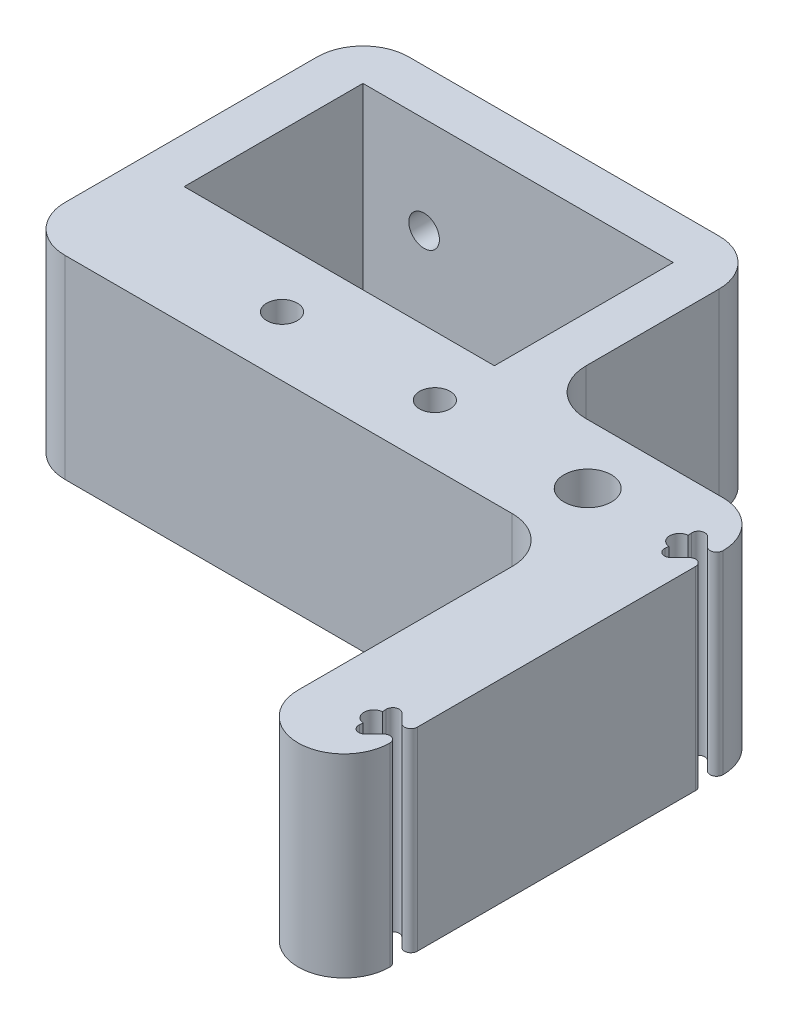
SolidWorks part; units mm, degrees
material "6061 Alloy"
ref_plane "Front Plane" through (0, 0, 0) normal (0, 0, 1) x (1, 0, 0)
ref_plane "Top Plane" through (0, 0, 0) normal (0, 1, 0) x (1, 0, 0)
ref_plane "Right Plane" through (0, 0, 0) normal (1, 0, 0) x (0, 0, -1)
sketch "Sketch1" plane through (0, 0, 0) normal (0, 1, 0) x (1, 0, 0)
  line L0 (0, 0) -> (-4, 0) construction
  line L1 (-4, 0) -> (-4.0553, 0.6326) construction
  line L2 (-4.0553, 0.6326) -> (-4.0758, 0.8669)
  line L3 (-3.3615, 1.2) -> (-2.7615, 0.6)
  line L4 (-4, 0) -> (-3.0808, 0.9192) construction
  line L5 (-6.465, 0.8965) -> (-2.465, 0.8965) construction
  line L6 (-4.0553, -0.6326) -> (-4.0758, -0.8669)
  line L7 (-3.3615, -1.2) -> (-2.7615, -0.6)
  line L47 (-4.0553, 20.6326) -> (-4.0758, 20.8669)
  line L48 (-3.3615, 21.2) -> (-2.7615, 20.6)
  line L49 (-4.0553, 19.3674) -> (-4.0758, 19.1331)
  line L50 (-3.3615, 18.8) -> (-2.7615, 19.4)
  line L53 (-4, 20) -> (-4.0553, 20.6326) construction
  line L54 (-4, 20) -> (-3.0808, 20.9192) construction
  line L55 (-4.0553, 0.6326) -> (-4.0553, 20.6326) construction
  line L67 (-7.2335, 20) -> (-10.075, 20) construction
  line L72 (-2.0456, 0.8965) -> (-2.0456, 19.1035)
  line L73 (-20, 35.5965) -> (-20, 23.8965)
  line L74 (-5.0456, 23.8965) -> (-14, 23.8965)
  line L75 (-2.465, -0.8965) -> (-5.0456, -0.8965) construction
  line L76 (-5.0456, 20.8965) -> (-2.465, 20.8965) construction
  line L78 (-8.0456, -0.8965) -> (-8.0456, 13.1035)
  line L79 (-11.0456, 16.1035) -> (-40.3, 16.1035)
  line L81 (-17, 26.8965) -> (-17, 35.5965)
  line L82 (-20, 38.5965) -> (-40.3, 38.5965)
  line L83 (-20, 23.8965) -> (-40.3, 23.8965)
  line L84 (-20, 35.5965) -> (-40.3, 35.5965)
  line L87 (-40.3, 35.5965) -> (-40.3, 23.8965)
  line L88 (-43.3, 19.1035) -> (-43.3, 35.5965)
  line L89 (-10, 20) -> (-10, 23.8965) construction
  line L90 (-10, 20) -> (-10, 16.1035) construction
  circle A0 centre (-4, 0) radius 0.635 construction
  arc A1 (-4.0758, 0.8669) -> (-3.3615, 1.2) centre (-3.6581, 0.9035) cw
  arc A2 (-2.7615, 0.6) -> (-2.0456, 0.8965) centre (-2.465, 0.8965) ccw
  arc A4 (-4.0553, 0.6326) -> (-4.0553, -0.6326) centre (-4, 0) ccw
  arc A5 (-4.0758, -0.8669) -> (-3.3615, -1.2) centre (-3.6581, -0.9035) ccw
  arc A6 (-2.7615, -0.6) -> (-2.0456, -0.8965) centre (-2.465, -0.8965) cw
  arc A87 (-4.0758, 20.8669) -> (-3.3615, 21.2) centre (-3.6581, 20.9035) cw
  arc A88 (-2.7615, 20.6) -> (-2.0456, 20.8965) centre (-2.465, 20.8965) ccw
  arc A89 (-4.0553, 20.6326) -> (-4.0553, 19.3674) centre (-4, 20) ccw
  arc A90 (-4.0758, 19.1331) -> (-3.3615, 18.8) centre (-3.6581, 19.0965) ccw
  arc A91 (-2.7615, 19.4) -> (-2.0456, 19.1035) centre (-2.465, 19.1035) cw
  circle A92 centre (-4, 20) radius 0.635 construction
  arc A93 (-2.0456, -0.8965) -> (-8.0456, -0.8965) centre (-5.0456, -0.8965) cw
  arc A105 (-8.0456, 13.1035) -> (-11.0456, 16.1035) centre (-11.0456, 13.1035) ccw
  arc A110 (-2.0456, 20.8965) -> (-5.0456, 23.8965) centre (-5.0456, 20.8965) ccw
  circle A111 centre (-20, 20) radius 1
  circle A114 centre (-10, 20) radius 1.55
  arc A115 (-14, 23.8965) -> (-17, 26.8965) centre (-14, 26.8965) cw
  arc A116 (-17, 35.5965) -> (-20, 38.5965) centre (-20, 35.5965) ccw
  circle A118 centre (-30, 20) radius 1
  arc A119 (-40.3, 16.1035) -> (-43.3, 19.1035) centre (-40.3, 19.1035) cw
  arc A120 (-40.3, 38.5965) -> (-43.3, 35.5965) centre (-40.3, 35.5965) ccw
  point P0 (0, 0)
  dimension "D1" = 1.27
  dimension "D16" = 16
  dimension "D13" = 20.3
  dimension "D8" = 2
  dimension "D15" = 3.1
  dimension "D10" = 10
  dimension "D11" = 3
  dimension "D9" = 20
  dimension "D14" = 2
  dimension "D17" = 10
  dimension "D12" = 11.7
  dimension "D2" = 4
  dimension "D3" = 95
  dimension "D4" = 45
  dimension "D5" = 1.2
  dimension "D6" = 1.3
  dimension "D7" = 0.6
  dimension "D18" = 6
extrude "Boss-Extrude1" add sketch "Sketch1" along normal blind 12.7
sketch "Sketch2" plane through (0, 0, -38.5965) normal (0, 0, -1) x (-1, 0, 0)
  line L0 (40.3, 6.35) -> (20, 6.35) construction
  line L1 (40.3, 12.7) -> (40.3, 0) construction
  line L2 (20, 12.7) -> (20, 0) construction
  circle A0 centre (36.3, 6.35) radius 1
  circle A1 centre (24, 6.35) radius 1
  point P10 (0, 0)
  point P11 (0, 0)
  point P12 (0, 0)
  dimension "D1" = 2
  dimension "D2" = 4
  dimension "D3" = 4
extrude "Cut-Extrude1" cut sketch "Sketch2" against normal up to next
